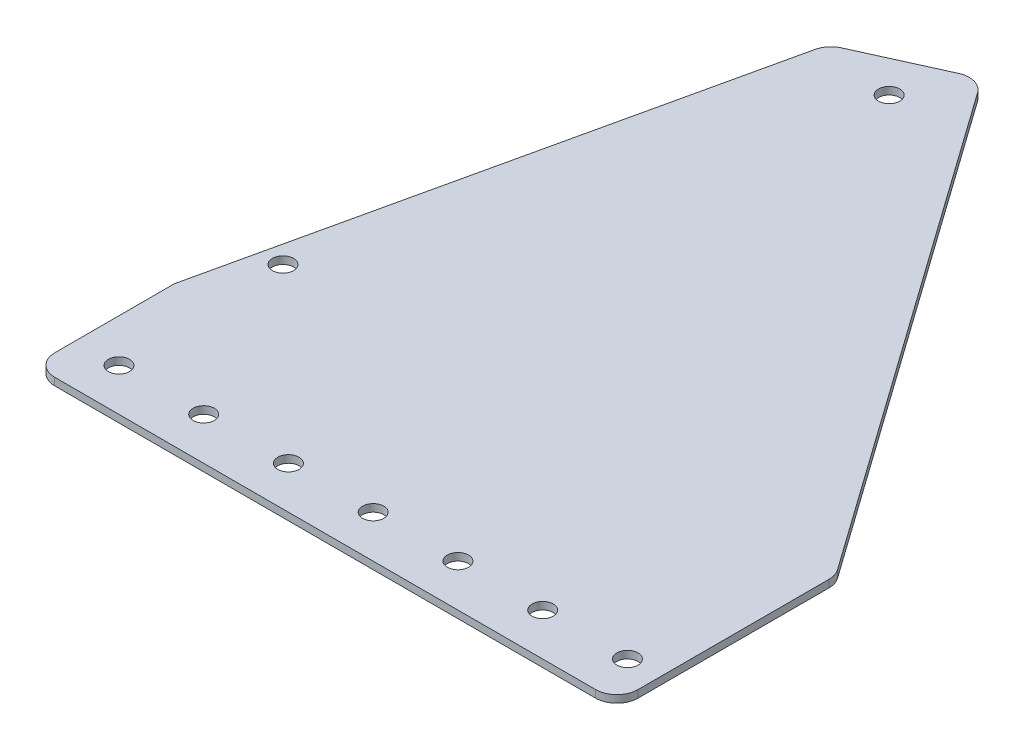
SolidWorks part; units mm, degrees
ref_plane "Front Plane" through (0, 0, 0) normal (0, 0, 1) x (1, 0, 0)
ref_plane "Top Plane" through (0, 0, 0) normal (0, 1, 0) x (1, 0, 0)
ref_plane "Right Plane" through (0, 0, 0) normal (1, 0, 0) x (0, 0, -1)
sketch "Sketch1" plane through (0, 0, 0) normal (0, 1, 0) x (1, 0, 0)
  line L0 (-67.5, 116.9134) -> (-64, 0) construction
  line L2 (-16, -8) -> (6, -8)
  line L6 (-63.5135, 117.4231) -> (-2, 30.797)
  line L8 (-81.5242, 119.3123) -> (-61.4758, 128.3709)
  line L9 (-61.4758, 128.3709) -> (6, 33.3484)
  line L10 (-67.5, 116.9134) -> (0, 0) construction
  line L11 (-67.5, 116.9134) -> (-71.5, 123.8416) construction
  line L13 (6, -8) -> (-16, -8) construction
  line L17 (-2, 30.797) -> (-2, 8)
  line L23 (-81.5242, 119.3123) -> (-104.1269, 18.5896)
  line L24 (-104.1269, -8) -> (-86.0937, -8)
  line L27 (-86.0937, -8) -> (-16, -8)
  line L28 (-104.1269, -8) -> (-104.1269, 18.5896)
  line L29 (-96, 0) -> (-97.0217, 31.9837) construction
  line L33 (-2, 8) -> (-60.2377, 8)
  line L37 (6, 33.3484) -> (6, -8)
  line L38 (-60.2377, 8) -> (-63.5135, 117.4231)
  line L48 (-68.2413, 8) -> (-98.3042, 8)
  line L49 (-98.3042, 8) -> (-74.5924, 113.6656)
  line L50 (-74.5924, 113.6656) -> (-71.4471, 115.0868)
  line L52 (-71.4471, 115.0868) -> (-68.2413, 8)
  circle A0 centre (-16, 0) radius 2
  circle A2 centre (0, 0) radius 2
  circle A3 centre (-67.5, 116.9134) radius 2
  circle A4 centre (-32, 0) radius 2
  circle A5 centre (-48, 0) radius 2
  circle A6 centre (-64, 0) radius 2
  circle A7 centre (-80, 0) radius 2
  circle A8 centre (-96, 0) radius 2
  circle A11 centre (-97.0217, 31.9837) radius 2
  point P4 (0, 0)
  point P7 (0, 0)
  point P20 (-63.4802, 109.951)
  dimension "D2" = 4
  dimension "D15" = 4
  dimension "D3" = 4
  dimension "D4" = 6
  dimension "D5" = 4
  dimension "D6" = 8
  dimension "D7" = 135
  dimension "D8" = 8
  dimension "D9" = 8
  dimension "D10" = 8
  dimension "D12" = 32
  dimension "D13" = 16
  dimension "D14" = 8
  dimension "D11" = 6
extrude "Boss-Extrude1" add sketch "Sketch1" along normal blind 1.4077 contours L37 L9 L8 L23 L28 L24 L27 L2 A11 A8 A7 A6 A5 A4 A3 A2 A0 L33 L38 L6 L17 L50 L52 L48 L49
fillet "Fillet2" radius 4 6 edges at (-61.4758, 0.7039, -128.3709) (-81.5242, 0.7039, -119.3123) (-104.1269, 0.7039, 8) (-104.1269, 0.7039, -18.5896) (6, 0.7039, 8) (6, 0.7039, -33.3484)
